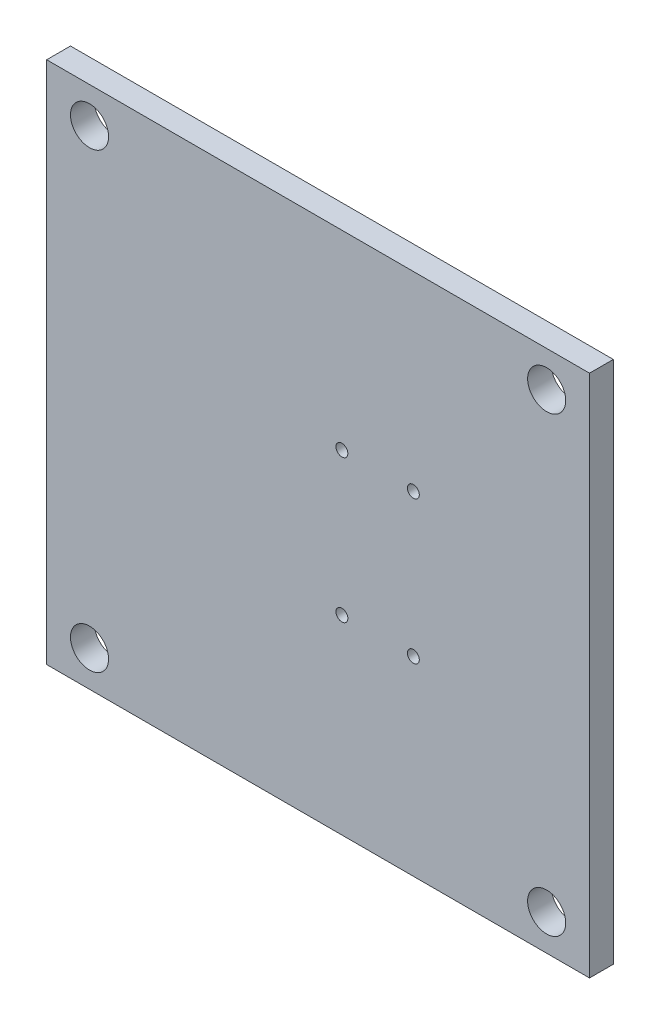
SolidWorks part; units mm, degrees
ref_plane "前视基准面" through (0, 0, 0) normal (0, 0, 1) x (1, 0, 0)
ref_plane "上视基准面" through (0, 0, 0) normal (0, 1, 0) x (1, 0, 0)
ref_plane "右视基准面" through (0, 0, 0) normal (1, 0, 0) x (0, 0, -1)
sketch "草图1" plane through (0, 0, 0) normal (0, 0, 1) x (1, 0, 0)
  line L0 (-1000, 0) -> (49000, 0) construction
  line L1 (-57, 55) -> (57, 55)
  line L2 (-57, 55) -> (-57, -55)
  line L3 (-57, -55) -> (57, -55)
  line L4 (57, 55) -> (57, -55)
  line L5 (-57, 55) -> (57, -55) construction
  line L6 (-57, -55) -> (57, 55) construction
  line L7 (0, -1000) -> (0, 49000) construction
  circle A0 centre (-23, 9) radius 2 construction
  circle A1 centre (-23, -9) radius 2 construction
  circle A3 centre (0, 47.5) radius 2 construction
  point P0 (0, 0)
  dimension "D3" = 46
  dimension "D4" = 23
  dimension "D7" = 7.5
  dimension "D1" = 110
  dimension "D2" = 114
extrude "凸台-拉伸2" add sketch "草图1" along normal mid plane 5
sketch "草图2" plane through (0, 0, 2.5) normal (0, 0, 1) x (1, 0, 0)
  line L0 (-1000, 0) -> (49000, 0) construction
  line L1 (0, -1000) -> (0, 49000) construction
  line L2 (-57, 55) -> (-57, -55) construction
  line L3 (57, 55) -> (-57, 55) construction
  circle A0 centre (-48, 47.5) radius 4
  dimension "D1" = 9
  dimension "D2" = 7.5
extrude "切除-拉伸1" cut sketch "草图2" against normal through all
mirror "镜向1" about plane through (0, 0, 0) normal (0, 1, 0) of "切除-拉伸1"
mirror "镜向2" about plane through (0, 0, 0) normal (1, 0, 0) of "镜向1", "切除-拉伸1"
sketch "草图3" plane through (0, 0, 2.5) normal (0, 0, 1) x (1, 0, 0)
  line L0 (-17, -981.0238) -> (-17, 49018.9762) construction
  line L1 (57, -55) -> (57, 55) construction
  line L2 (-1000, 0) -> (49000, 0) construction
  circle A0 centre (5, 15) radius 2
  circle A1 centre (20, 15) radius 2
  dimension "D2" = 22
  dimension "D3" = 15
  dimension "D4" = 15
  dimension "D1" = 74
hole_wizard "M3 螺纹孔的螺纹孔钻头1" positions "3D草图1" profile "草图4" hole size "M3" standard "GB" end condition through all
sketch3d "3D草图1"
  point P0 (5, 15, 2.5)
  point P3 (20, 15, 2.5)
sketch "草图4" plane through (5, 15, 2.5) normal (1, 0, 0) x (0, -1, 0)
  line L0 (0, 0) -> (0, 5)
  line L1 (0, 5) -> (1.25, 5)
  line L2 (1.25, 5) -> (1.25, 0)
  line L5 (1.25, 0) -> (0, 0)
  line L11 (0, -6.35) -> (0, 107.95) construction
  dimension "通孔孔直径" = 2.5
  dimension "通孔孔深度" = 5
mirror "镜向3" about plane through (0, 0, 0) normal (0, 1, 0) of "M3 螺纹孔的螺纹孔钻头1"
